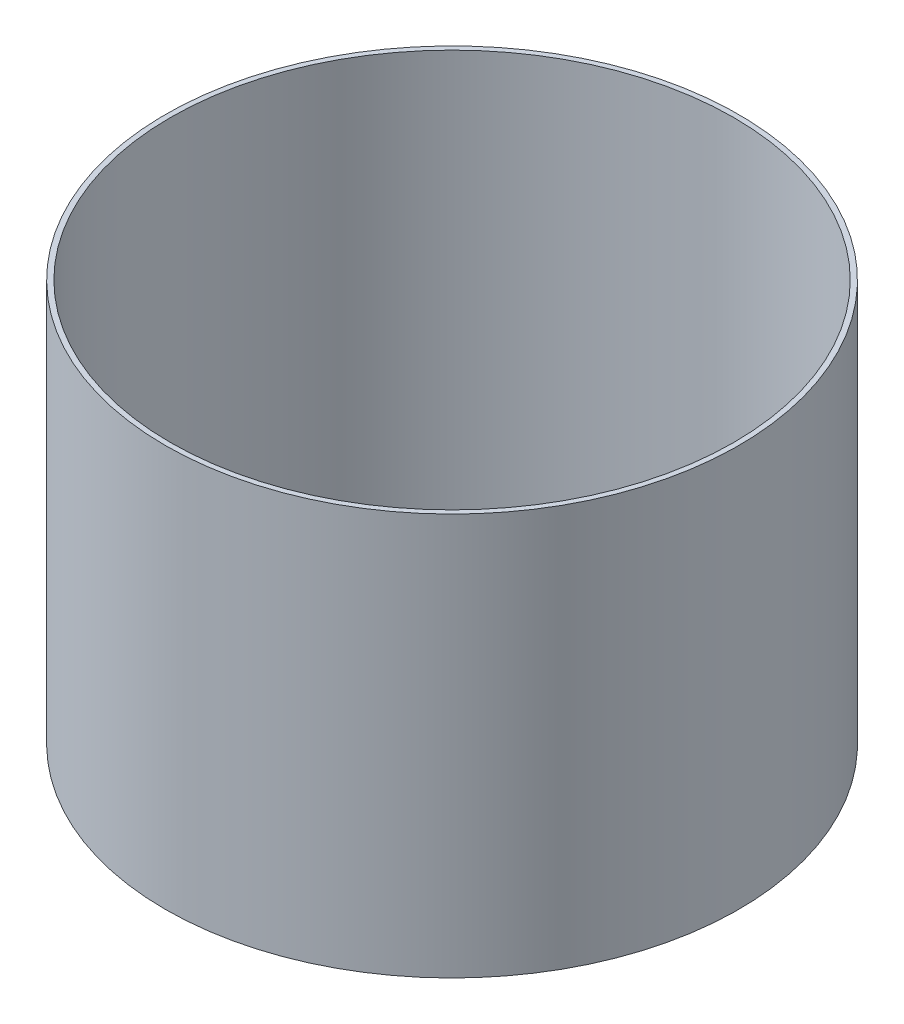
SolidWorks part; units mm, degrees
ref_plane "Front Plane" through (0, 0, 0) normal (0, 0, 1) x (1, 0, 0)
ref_plane "Top Plane" through (0, 0, 0) normal (0, 1, 0) x (1, 0, 0)
ref_plane "Right Plane" through (0, 0, 0) normal (1, 0, 0) x (0, 0, -1)
sketch "Sketch2" plane through (0, 0, 0) normal (0, 1, 0) x (1, 0, 0)
  circle A0 centre (0, 0) radius 71.12
  circle A1 centre (0, 0) radius 69.85
  dimension "D1" = 142.24
  dimension "D2" = 139.7
extrude "Extrude1" add sketch "Sketch2" against normal blind 99.6696
sketch "Sketch1" plane through (0, 0, 0) normal (0, 0, 1) x (1, 0, 0)
  line L1 (-228.6, 0) -> (228.6, 0)
  line L2 (-228.6, 0) -> (-228.6, -99.6718)
  line L3 (-228.6, -99.6718) -> (228.6, -99.6718)
  line L4 (228.6, 0) -> (228.6, -99.6718)
  line L416 (-215.864, -82.9078) -> (215.864, -82.9078) construction
  line L417 (215.864, -82.9078) -> (215.864, -66.7382) construction
  line L418 (215.864, -66.7382) -> (-215.864, -66.7382) construction
  line L419 (-215.864, -66.7382) -> (-215.864, -82.9078) construction
  line L420 (-202.6925, -66.7382) -> (-201.5763, -66.7382) construction
  line L421 (-201.5763, -66.7382) -> (-201.5763, -57.5942) construction
  line L422 (-201.5763, -57.5942) -> (-202.6925, -57.5942) construction
  line L423 (-202.6925, -57.5942) -> (-202.6925, -66.7382) construction
  line L424 (-175.7412, -66.7382) -> (-174.6251, -66.7382) construction
  line L425 (-174.6251, -66.7382) -> (-174.6251, -57.5942) construction
  line L426 (-174.6251, -57.5942) -> (-175.7412, -57.5942) construction
  line L427 (-175.7412, -57.5942) -> (-175.7412, -66.7382) construction
  line L428 (-148.79, -66.7382) -> (-147.6738, -66.7382) construction
  line L429 (-147.6738, -66.7382) -> (-147.6738, -57.5942) construction
  line L430 (-147.6738, -57.5942) -> (-148.79, -57.5942) construction
  line L431 (-148.79, -57.5942) -> (-148.79, -66.7382) construction
  line L432 (-121.8387, -66.7382) -> (-120.7225, -66.7382) construction
  line L433 (-120.7225, -66.7382) -> (-120.7225, -57.5942) construction
  line L434 (-120.7225, -57.5942) -> (-121.8387, -57.5942) construction
  line L435 (-121.8387, -57.5942) -> (-121.8387, -66.7382) construction
  line L436 (-94.8875, -66.7382) -> (-93.7713, -66.7382) construction
  line L437 (-93.7713, -66.7382) -> (-93.7713, -57.5942) construction
  line L438 (-93.7713, -57.5942) -> (-94.8875, -57.5942) construction
  line L439 (-94.8875, -57.5942) -> (-94.8875, -66.7382) construction
  line L440 (-67.9362, -66.7382) -> (-66.82, -66.7382) construction
  line L441 (-66.82, -66.7382) -> (-66.82, -57.5942) construction
  line L442 (-66.82, -57.5942) -> (-67.9362, -57.5942) construction
  line L443 (-67.9362, -57.5942) -> (-67.9362, -66.7382) construction
  line L444 (-40.985, -66.7382) -> (-39.8688, -66.7382) construction
  line L445 (-39.8688, -66.7382) -> (-39.8688, -57.5942) construction
  line L446 (-39.8688, -57.5942) -> (-40.985, -57.5942) construction
  line L447 (-40.985, -57.5942) -> (-40.985, -66.7382) construction
  line L448 (-14.0337, -66.7382) -> (-12.9175, -66.7382) construction
  line L449 (-12.9175, -66.7382) -> (-12.9175, -57.5942) construction
  line L450 (-12.9175, -57.5942) -> (-14.0337, -57.5942) construction
  line L451 (-14.0337, -57.5942) -> (-14.0337, -66.7382) construction
  line L452 (12.9175, -66.7382) -> (14.0337, -66.7382) construction
  line L453 (14.0337, -66.7382) -> (14.0337, -57.5942) construction
  line L454 (14.0337, -57.5942) -> (12.9175, -57.5942) construction
  line L455 (12.9175, -57.5942) -> (12.9175, -66.7382) construction
  line L456 (39.8688, -66.7382) -> (40.985, -66.7382) construction
  line L457 (40.985, -66.7382) -> (40.985, -57.5942) construction
  line L458 (40.985, -57.5942) -> (39.8688, -57.5942) construction
  line L459 (39.8688, -57.5942) -> (39.8688, -66.7382) construction
  line L460 (66.82, -66.7382) -> (67.9362, -66.7382) construction
  line L461 (67.9362, -66.7382) -> (67.9362, -57.5942) construction
  line L462 (67.9362, -57.5942) -> (66.82, -57.5942) construction
  line L463 (66.82, -57.5942) -> (66.82, -66.7382) construction
  line L464 (93.7713, -66.7382) -> (94.8875, -66.7382) construction
  line L465 (94.8875, -66.7382) -> (94.8875, -57.5942) construction
  line L466 (94.8875, -57.5942) -> (93.7713, -57.5942) construction
  line L467 (93.7713, -57.5942) -> (93.7713, -66.7382) construction
  line L468 (120.7225, -66.7382) -> (121.8387, -66.7382) construction
  line L469 (121.8387, -66.7382) -> (121.8387, -57.5942) construction
  line L470 (121.8387, -57.5942) -> (120.7225, -57.5942) construction
  line L471 (120.7225, -57.5942) -> (120.7225, -66.7382) construction
  line L472 (147.6738, -66.7382) -> (148.79, -66.7382) construction
  line L473 (148.79, -66.7382) -> (148.79, -57.5942) construction
  line L474 (148.79, -57.5942) -> (147.6738, -57.5942) construction
  line L475 (147.6738, -57.5942) -> (147.6738, -66.7382) construction
  line L476 (174.6251, -66.7382) -> (175.7412, -66.7382) construction
  line L477 (175.7412, -66.7382) -> (175.7412, -57.5942) construction
  line L478 (175.7412, -57.5942) -> (174.6251, -57.5942) construction
  line L479 (174.6251, -57.5942) -> (174.6251, -66.7382) construction
  line L480 (201.5763, -66.7382) -> (202.6925, -66.7382) construction
  line L481 (202.6925, -66.7382) -> (202.6925, -57.5942) construction
  line L482 (202.6925, -57.5942) -> (201.5763, -57.5942) construction
  line L483 (201.5763, -57.5942) -> (201.5763, -66.7382) construction
  line L484 (-201.5763, -57.5942) -> (-175.7412, -57.5942) construction
  line L485 (-175.7412, -57.5942) -> (-175.7412, -56.478) construction
  line L486 (-175.7412, -56.478) -> (-201.5763, -56.478) construction
  line L487 (-201.5763, -56.478) -> (-201.5763, -57.5942) construction
  line L488 (-147.6738, -57.5942) -> (-121.8387, -57.5942) construction
  line L489 (-121.8387, -57.5942) -> (-121.8387, -56.478) construction
  line L490 (-121.8387, -56.478) -> (-147.6738, -56.478) construction
  line L491 (-147.6738, -56.478) -> (-147.6738, -57.5942) construction
  line L492 (-93.7713, -57.5942) -> (-67.9361, -57.5942) construction
  line L493 (-67.9361, -57.5942) -> (-67.9361, -56.478) construction
  line L494 (-67.9361, -56.478) -> (-93.7713, -56.478) construction
  line L495 (-93.7713, -56.478) -> (-93.7713, -57.5942) construction
  line L496 (-39.8687, -57.5942) -> (-14.0336, -57.5942) construction
  line L497 (-14.0336, -57.5942) -> (-14.0336, -56.478) construction
  line L498 (-14.0336, -56.478) -> (-39.8687, -56.478) construction
  line L499 (-39.8687, -56.478) -> (-39.8687, -57.5942) construction
  line L500 (14.0336, -57.5942) -> (39.8687, -57.5942) construction
  line L501 (39.8687, -57.5942) -> (39.8687, -56.478) construction
  line L502 (39.8687, -56.478) -> (14.0336, -56.478) construction
  line L503 (14.0336, -56.478) -> (14.0336, -57.5942) construction
  line L504 (67.9361, -57.5942) -> (93.7713, -57.5942) construction
  line L505 (93.7713, -57.5942) -> (93.7713, -56.478) construction
  line L506 (93.7713, -56.478) -> (67.9361, -56.478) construction
  line L507 (67.9361, -56.478) -> (67.9361, -57.5942) construction
  line L508 (121.8387, -57.5942) -> (147.6738, -57.5942) construction
  line L509 (147.6738, -57.5942) -> (147.6738, -56.478) construction
  line L510 (147.6738, -56.478) -> (121.8387, -56.478) construction
  line L511 (121.8387, -56.478) -> (121.8387, -57.5942) construction
  line L512 (175.7412, -57.5942) -> (201.5763, -57.5942) construction
  line L513 (201.5763, -57.5942) -> (201.5763, -56.478) construction
  line L514 (201.5763, -56.478) -> (175.7412, -56.478) construction
  line L515 (175.7412, -56.478) -> (175.7412, -57.5942) construction
  line L516 (-190.8513, -57.5942) -> (-186.4661, -57.5942) construction
  line L517 (-186.4661, -57.5942) -> (-186.4661, -47.334) construction
  line L518 (-186.4661, -47.334) -> (-190.8513, -47.334) construction
  line L519 (-190.8513, -47.334) -> (-190.8513, -57.5942) construction
  line L520 (-136.9488, -57.5942) -> (-132.5636, -57.5942) construction
  line L521 (-132.5636, -57.5942) -> (-132.5636, -47.334) construction
  line L522 (-132.5636, -47.334) -> (-136.9488, -47.334) construction
  line L523 (-136.9488, -47.334) -> (-136.9488, -57.5942) construction
  line L524 (-83.0464, -57.5942) -> (-78.6611, -57.5942) construction
  line L525 (-78.6611, -57.5942) -> (-78.6611, -47.334) construction
  line L526 (-78.6611, -47.334) -> (-83.0464, -47.334) construction
  line L527 (-83.0464, -47.334) -> (-83.0464, -57.5942) construction
  line L528 (-29.1439, -57.5942) -> (-24.7585, -57.5942) construction
  line L529 (-24.7585, -57.5942) -> (-24.7585, -47.334) construction
  line L530 (-24.7585, -47.334) -> (-29.1439, -47.334) construction
  line L531 (-29.1439, -47.334) -> (-29.1439, -57.5942) construction
  line L532 (24.7585, -57.5942) -> (29.1439, -57.5942) construction
  line L533 (29.1439, -57.5942) -> (29.1439, -47.334) construction
  line L534 (29.1439, -47.334) -> (24.7585, -47.334) construction
  line L535 (24.7585, -47.334) -> (24.7585, -57.5942) construction
  line L536 (78.6611, -57.5942) -> (83.0464, -57.5942) construction
  line L537 (83.0464, -57.5942) -> (83.0464, -47.334) construction
  line L538 (83.0464, -47.334) -> (78.6611, -47.334) construction
  line L539 (78.6611, -47.334) -> (78.6611, -57.5942) construction
  line L540 (132.5636, -57.5942) -> (136.9488, -57.5942) construction
  line L541 (136.9488, -57.5942) -> (136.9488, -47.334) construction
  line L542 (136.9488, -47.334) -> (132.5636, -47.334) construction
  line L543 (132.5636, -47.334) -> (132.5636, -57.5942) construction
  line L544 (186.4661, -57.5942) -> (190.8513, -57.5942) construction
  line L545 (190.8513, -57.5942) -> (190.8513, -47.334) construction
  line L546 (190.8513, -47.334) -> (186.4661, -47.334) construction
  line L547 (186.4661, -47.334) -> (186.4661, -57.5942) construction
  line L548 (-186.466, -47.334) -> (-177.9096, -47.334) construction
  line L549 (-177.9096, -47.334) -> (-177.9096, -42.9487) construction
  line L550 (-177.9096, -42.9487) -> (-186.466, -42.9487) construction
  line L551 (-186.466, -42.9487) -> (-186.466, -47.334) construction
  line L552 (-145.5055, -47.334) -> (-136.9489, -47.334) construction
  line L553 (-136.9489, -47.334) -> (-136.9489, -42.9487) construction
  line L554 (-136.9489, -42.9487) -> (-145.5055, -42.9487) construction
  line L555 (-145.5055, -42.9487) -> (-145.5055, -47.334) construction
  line L556 (-78.6611, -47.334) -> (-70.1045, -47.334) construction
  line L557 (-70.1045, -47.334) -> (-70.1045, -42.9487) construction
  line L558 (-70.1045, -42.9487) -> (-78.6611, -42.9487) construction
  line L559 (-78.6611, -42.9487) -> (-78.6611, -47.334) construction
  line L560 (-37.7005, -47.334) -> (-29.1439, -47.334) construction
  line L561 (-29.1439, -47.334) -> (-29.1439, -42.9487) construction
  line L562 (-29.1439, -42.9487) -> (-37.7005, -42.9487) construction
  line L563 (-37.7005, -42.9487) -> (-37.7005, -47.334) construction
  line L564 (29.1439, -47.334) -> (37.7005, -47.334) construction
  line L565 (37.7005, -47.334) -> (37.7005, -42.9487) construction
  line L566 (37.7005, -42.9487) -> (29.1439, -42.9487) construction
  line L567 (29.1439, -42.9487) -> (29.1439, -47.334) construction
  line L568 (70.1045, -47.334) -> (78.6611, -47.334) construction
  line L569 (78.6611, -47.334) -> (78.6611, -42.9487) construction
  line L570 (78.6611, -42.9487) -> (70.1045, -42.9487) construction
  line L571 (70.1045, -42.9487) -> (70.1045, -47.334) construction
  line L572 (136.9489, -47.334) -> (145.5055, -47.334) construction
  line L573 (145.5055, -47.334) -> (145.5055, -42.9487) construction
  line L574 (145.5055, -42.9487) -> (136.9489, -42.9487) construction
  line L575 (136.9489, -42.9487) -> (136.9489, -47.334) construction
  line L576 (177.9096, -47.334) -> (186.466, -47.334) construction
  line L577 (186.466, -47.334) -> (186.466, -42.9487) construction
  line L578 (186.466, -42.9487) -> (177.9096, -42.9487) construction
  line L579 (177.9096, -42.9487) -> (177.9096, -47.334) construction
  line L580 (-177.9095, -46.538) -> (-168.0714, -46.538) construction
  line L581 (-168.0714, -46.538) -> (-168.0714, -43.7446) construction
  line L582 (-168.0714, -43.7446) -> (-177.9095, -43.7446) construction
  line L583 (-177.9095, -43.7446) -> (-177.9095, -46.538) construction
  line L584 (-155.3435, -46.538) -> (-145.5054, -46.538) construction
  line L585 (-145.5054, -46.538) -> (-145.5054, -43.7446) construction
  line L586 (-145.5054, -43.7446) -> (-155.3435, -43.7446) construction
  line L587 (-155.3435, -43.7446) -> (-155.3435, -46.538) construction
  line L588 (-70.1045, -46.538) -> (-60.2665, -46.538) construction
  line L589 (-60.2665, -46.538) -> (-60.2665, -43.7446) construction
  line L590 (-60.2665, -43.7446) -> (-70.1045, -43.7446) construction
  line L591 (-70.1045, -43.7446) -> (-70.1045, -46.538) construction
  line L592 (-47.5385, -46.538) -> (-37.7005, -46.538) construction
  line L593 (-37.7005, -46.538) -> (-37.7005, -43.7446) construction
  line L594 (-37.7005, -43.7446) -> (-47.5385, -43.7446) construction
  line L595 (-47.5385, -43.7446) -> (-47.5385, -46.538) construction
  line L596 (37.7005, -46.538) -> (47.5385, -46.538) construction
  line L597 (47.5385, -46.538) -> (47.5385, -43.7446) construction
  line L598 (47.5385, -43.7446) -> (37.7005, -43.7446) construction
  line L599 (37.7005, -43.7446) -> (37.7005, -46.538) construction
  line L600 (60.2665, -46.538) -> (70.1045, -46.538) construction
  line L601 (70.1045, -46.538) -> (70.1045, -43.7446) construction
  line L602 (70.1045, -43.7446) -> (60.2665, -43.7446) construction
  line L603 (60.2665, -43.7446) -> (60.2665, -46.538) construction
  line L604 (145.5054, -46.538) -> (155.3435, -46.538) construction
  line L605 (155.3435, -46.538) -> (155.3435, -43.7446) construction
  line L606 (155.3435, -43.7446) -> (145.5054, -43.7446) construction
  line L607 (145.5054, -43.7446) -> (145.5054, -46.538) construction
  line L608 (168.0714, -46.538) -> (177.9095, -46.538) construction
  line L609 (177.9095, -46.538) -> (177.9095, -43.7446) construction
  line L610 (177.9095, -43.7446) -> (168.0714, -43.7446) construction
  line L611 (168.0714, -43.7446) -> (168.0714, -46.538) construction
  line L612 (-168.0714, -45.9607) -> (-155.3436, -45.9607) construction
  line L613 (-155.3436, -45.9607) -> (-155.3436, -44.322) construction
  line L614 (-155.3436, -44.322) -> (-168.0714, -44.322) construction
  line L615 (-168.0714, -44.322) -> (-168.0714, -45.9607) construction
  line L616 (-60.2665, -45.9607) -> (-47.5385, -45.9607) construction
  line L617 (-47.5385, -45.9607) -> (-47.5385, -44.322) construction
  line L618 (-47.5385, -44.322) -> (-60.2665, -44.322) construction
  line L619 (-60.2665, -44.322) -> (-60.2665, -45.9607) construction
  line L620 (47.5385, -45.9607) -> (60.2665, -45.9607) construction
  line L621 (60.2665, -45.9607) -> (60.2665, -44.322) construction
  line L622 (60.2665, -44.322) -> (47.5385, -44.322) construction
  line L623 (47.5385, -44.322) -> (47.5385, -45.9607) construction
  line L624 (155.3436, -45.9607) -> (168.0714, -45.9607) construction
  line L625 (168.0714, -45.9607) -> (168.0714, -44.322) construction
  line L626 (168.0714, -44.322) -> (155.3436, -44.322) construction
  line L627 (155.3436, -44.322) -> (155.3436, -45.9607) construction
  line L628 (-164.5244, -44.322) -> (-158.8906, -44.322) construction
  line L629 (-158.8906, -44.322) -> (-158.8906, -35.178) construction
  line L630 (-158.8906, -35.178) -> (-164.5244, -35.178) construction
  line L631 (-164.5244, -35.178) -> (-164.5244, -44.322) construction
  line L632 (-56.7194, -44.322) -> (-51.0856, -44.322) construction
  line L633 (-51.0856, -44.322) -> (-51.0856, -35.178) construction
  line L634 (-51.0856, -35.178) -> (-56.7194, -35.178) construction
  line L635 (-56.7194, -35.178) -> (-56.7194, -44.322) construction
  line L636 (51.0856, -44.322) -> (56.7194, -44.322) construction
  line L637 (56.7194, -44.322) -> (56.7194, -35.178) construction
  line L638 (56.7194, -35.178) -> (51.0856, -35.178) construction
  line L639 (51.0856, -35.178) -> (51.0856, -44.322) construction
  line L640 (158.8906, -44.322) -> (164.5244, -44.322) construction
  line L641 (164.5244, -44.322) -> (164.5244, -35.178) construction
  line L642 (164.5244, -35.178) -> (158.8906, -35.178) construction
  line L643 (158.8906, -35.178) -> (158.8906, -44.322) construction
  line L644 (-158.8906, -35.178) -> (-131.3922, -35.178) construction
  line L645 (-131.3922, -35.178) -> (-131.3922, -29.5443) construction
  line L646 (-131.3922, -29.5443) -> (-158.8906, -29.5443) construction
  line L647 (-158.8906, -29.5443) -> (-158.8906, -35.178) construction
  line L648 (-84.2178, -35.178) -> (-56.7194, -35.178) construction
  line L649 (-56.7194, -35.178) -> (-56.7194, -29.5443) construction
  line L650 (-56.7194, -29.5443) -> (-84.2178, -29.5443) construction
  line L651 (-84.2178, -29.5443) -> (-84.2178, -35.178) construction
  line L652 (56.7194, -35.178) -> (84.2178, -35.178) construction
  line L653 (84.2178, -35.178) -> (84.2178, -29.5443) construction
  line L654 (84.2178, -29.5443) -> (56.7194, -29.5443) construction
  line L655 (56.7194, -29.5443) -> (56.7194, -35.178) construction
  line L656 (131.3922, -35.178) -> (158.8906, -35.178) construction
  line L657 (158.8906, -35.178) -> (158.8906, -29.5443) construction
  line L658 (158.8906, -29.5443) -> (131.3922, -29.5443) construction
  line L659 (131.3922, -29.5443) -> (131.3922, -35.178) construction
  line L660 (-131.3922, -33.9769) -> (-121.3448, -33.9769) construction
  line L661 (-121.3448, -33.9769) -> (-121.3448, -30.7453) construction
  line L662 (-121.3448, -30.7453) -> (-131.3922, -30.7453) construction
  line L663 (-131.3922, -30.7453) -> (-131.3922, -33.9769) construction
  line L664 (-94.2652, -33.9769) -> (-84.2178, -33.9769) construction
  line L665 (-84.2178, -33.9769) -> (-84.2178, -30.7453) construction
  line L666 (-84.2178, -30.7453) -> (-94.2652, -30.7453) construction
  line L667 (-94.2652, -30.7453) -> (-94.2652, -33.9769) construction
  line L668 (84.2178, -33.9769) -> (94.2652, -33.9769) construction
  line L669 (94.2652, -33.9769) -> (94.2652, -30.7453) construction
  line L670 (94.2652, -30.7453) -> (84.2178, -30.7453) construction
  line L671 (84.2178, -30.7453) -> (84.2178, -33.9769) construction
  line L672 (121.3448, -33.9769) -> (131.3922, -33.9769) construction
  line L673 (131.3922, -33.9769) -> (131.3922, -30.7453) construction
  line L674 (131.3922, -30.7453) -> (121.3448, -30.7453) construction
  line L675 (121.3448, -30.7453) -> (121.3448, -33.9769) construction
  line L676 (-121.3448, -33.1804) -> (-94.2652, -33.1804) construction
  line L677 (-94.2652, -33.1804) -> (-94.2652, -31.5418) construction
  line L678 (-94.2652, -31.5418) -> (-121.3448, -31.5418) construction
  line L679 (-121.3448, -31.5418) -> (-121.3448, -33.1804) construction
  line L680 (94.2652, -33.1804) -> (121.3448, -33.1804) construction
  line L681 (121.3448, -33.1804) -> (121.3448, -31.5418) construction
  line L682 (121.3448, -31.5418) -> (94.2652, -31.5418) construction
  line L683 (94.2652, -31.5418) -> (94.2652, -33.1804) construction
  line L684 (-110.6219, -31.5418) -> (-104.9881, -31.5418) construction
  line L685 (-104.9881, -31.5418) -> (-104.9881, -22.3978) construction
  line L686 (-104.9881, -22.3978) -> (-110.6219, -22.3978) construction
  line L687 (-110.6219, -22.3978) -> (-110.6219, -31.5418) construction
  line L688 (104.9881, -31.5418) -> (110.6219, -31.5418) construction
  line L689 (110.6219, -31.5418) -> (110.6219, -22.3978) construction
  line L690 (110.6219, -22.3978) -> (104.9881, -22.3978) construction
  line L691 (104.9881, -22.3978) -> (104.9881, -31.5418) construction
  line L692 (-104.9881, -22.3978) -> (-41.5547, -22.3978) construction
  line L693 (-41.5547, -22.3978) -> (-41.5547, -16.764) construction
  line L694 (-41.5547, -16.764) -> (-104.9881, -16.764) construction
  line L695 (-104.9881, -16.764) -> (-104.9881, -22.3978) construction
  line L696 (41.5547, -22.3978) -> (104.9881, -22.3978) construction
  line L697 (104.9881, -22.3978) -> (104.9881, -16.764) construction
  line L698 (104.9881, -16.764) -> (41.5547, -16.764) construction
  line L699 (41.5547, -16.764) -> (41.5547, -22.3978) construction
  line L700 (-41.5547, -21.1967) -> (-31.5072, -21.1967) construction
  line L701 (-31.5072, -21.1967) -> (-31.5072, -17.9651) construction
  line L702 (-31.5072, -17.9651) -> (-41.5547, -17.9651) construction
  line L703 (-41.5547, -17.9651) -> (-41.5547, -21.1967) construction
  line L704 (31.5072, -21.1967) -> (41.5547, -21.1967) construction
  line L705 (41.5547, -21.1967) -> (41.5547, -17.9651) construction
  line L706 (41.5547, -17.9651) -> (31.5072, -17.9651) construction
  line L707 (31.5072, -17.9651) -> (31.5072, -21.1967) construction
  line L708 (-31.5073, -20.4003) -> (31.5073, -20.4003) construction
  line L709 (31.5073, -20.4003) -> (31.5073, -18.7616) construction
  line L710 (31.5073, -18.7616) -> (-31.5073, -18.7616) construction
  line L711 (-31.5073, -18.7616) -> (-31.5073, -20.4003) construction
  line L712 (-202.1344, -57.5942) -> (-201.5762, -57.5942) construction
  line L713 (-201.5762, -57.5942) -> (-201.5762, -57.0361) construction
  line L714 (-201.5762, -57.0361) -> (-202.1344, -57.0361) construction
  line L715 (-202.1344, -57.0361) -> (-202.1344, -57.5942) construction
  line L716 (-175.7412, -57.5942) -> (-175.183, -57.5942) construction
  line L717 (-175.183, -57.5942) -> (-175.183, -57.0361) construction
  line L718 (-175.183, -57.0361) -> (-175.7412, -57.0361) construction
  line L719 (-175.7412, -57.0361) -> (-175.7412, -57.5942) construction
  line L720 (-148.2319, -57.5942) -> (-147.6737, -57.5942) construction
  line L721 (-147.6737, -57.5942) -> (-147.6737, -57.0361) construction
  line L722 (-147.6737, -57.0361) -> (-148.2319, -57.0361) construction
  line L723 (-148.2319, -57.0361) -> (-148.2319, -57.5942) construction
  line L724 (-121.8387, -57.5942) -> (-121.2806, -57.5942) construction
  line L725 (-121.2806, -57.5942) -> (-121.2806, -57.0361) construction
  line L726 (-121.2806, -57.0361) -> (-121.8387, -57.0361) construction
  line L727 (-121.8387, -57.0361) -> (-121.8387, -57.5942) construction
  line L728 (-94.3293, -57.5942) -> (-93.7712, -57.5942) construction
  line L729 (-93.7712, -57.5942) -> (-93.7712, -57.0361) construction
  line L730 (-93.7712, -57.0361) -> (-94.3293, -57.0361) construction
  line L731 (-94.3293, -57.0361) -> (-94.3293, -57.5942) construction
  line L732 (-67.9361, -57.5942) -> (-67.3781, -57.5942) construction
  line L733 (-67.3781, -57.5942) -> (-67.3781, -57.0361) construction
  line L734 (-67.3781, -57.0361) -> (-67.9361, -57.0361) construction
  line L735 (-67.9361, -57.0361) -> (-67.9361, -57.5942) construction
  line L736 (-40.4268, -57.5942) -> (-39.8687, -57.5942) construction
  line L737 (-39.8687, -57.5942) -> (-39.8687, -57.0361) construction
  line L738 (-39.8687, -57.0361) -> (-40.4268, -57.0361) construction
  line L739 (-40.4268, -57.0361) -> (-40.4268, -57.5942) construction
  line L740 (-14.0336, -57.5942) -> (-13.4756, -57.5942) construction
  line L741 (-13.4756, -57.5942) -> (-13.4756, -57.0361) construction
  line L742 (-13.4756, -57.0361) -> (-14.0336, -57.0361) construction
  line L743 (-14.0336, -57.0361) -> (-14.0336, -57.5942) construction
  line L744 (13.4756, -57.5942) -> (14.0336, -57.5942) construction
  line L745 (14.0336, -57.5942) -> (14.0336, -57.0361) construction
  line L746 (14.0336, -57.0361) -> (13.4756, -57.0361) construction
  line L747 (13.4756, -57.0361) -> (13.4756, -57.5942) construction
  line L748 (39.8687, -57.5942) -> (40.4268, -57.5942) construction
  line L749 (40.4268, -57.5942) -> (40.4268, -57.0361) construction
  line L750 (40.4268, -57.0361) -> (39.8687, -57.0361) construction
  line L751 (39.8687, -57.0361) -> (39.8687, -57.5942) construction
  line L752 (67.3781, -57.5942) -> (67.9361, -57.5942) construction
  line L753 (67.9361, -57.5942) -> (67.9361, -57.0361) construction
  line L754 (67.9361, -57.0361) -> (67.3781, -57.0361) construction
  line L755 (67.3781, -57.0361) -> (67.3781, -57.5942) construction
  line L756 (93.7712, -57.5942) -> (94.3293, -57.5942) construction
  line L757 (94.3293, -57.5942) -> (94.3293, -57.0361) construction
  line L758 (94.3293, -57.0361) -> (93.7712, -57.0361) construction
  line L759 (93.7712, -57.0361) -> (93.7712, -57.5942) construction
  line L760 (121.2806, -57.5942) -> (121.8387, -57.5942) construction
  line L761 (121.8387, -57.5942) -> (121.8387, -57.0361) construction
  line L762 (121.8387, -57.0361) -> (121.2806, -57.0361) construction
  line L763 (121.2806, -57.0361) -> (121.2806, -57.5942) construction
  line L764 (147.6737, -57.5942) -> (148.2319, -57.5942) construction
  line L765 (148.2319, -57.5942) -> (148.2319, -57.0361) construction
  line L766 (148.2319, -57.0361) -> (147.6737, -57.0361) construction
  line L767 (147.6737, -57.0361) -> (147.6737, -57.5942) construction
  line L768 (175.183, -57.5942) -> (175.7412, -57.5942) construction
  line L769 (175.7412, -57.5942) -> (175.7412, -57.0361) construction
  line L770 (175.7412, -57.0361) -> (175.183, -57.0361) construction
  line L771 (175.183, -57.0361) -> (175.183, -57.5942) construction
  line L772 (201.5762, -57.5942) -> (202.1344, -57.5942) construction
  line L773 (202.1344, -57.5942) -> (202.1344, -57.0361) construction
  line L774 (202.1344, -57.0361) -> (201.5762, -57.0361) construction
  line L775 (201.5762, -57.0361) -> (201.5762, -57.5942) construction
  line L776 (-188.6588, -47.334) -> (-186.466, -47.334) construction
  line L777 (-186.466, -47.334) -> (-186.466, -45.1412) construction
  line L778 (-186.466, -45.1412) -> (-188.6588, -45.1412) construction
  line L779 (-188.6588, -45.1412) -> (-188.6588, -47.334) construction
  line L780 (-136.9489, -47.334) -> (-134.7563, -47.334) construction
  line L781 (-134.7563, -47.334) -> (-134.7563, -45.1412) construction
  line L782 (-134.7563, -45.1412) -> (-136.9489, -45.1412) construction
  line L783 (-136.9489, -45.1412) -> (-136.9489, -47.334) construction
  line L784 (-80.8538, -47.334) -> (-78.6611, -47.334) construction
  line L785 (-78.6611, -47.334) -> (-78.6611, -45.1412) construction
  line L786 (-78.6611, -45.1412) -> (-80.8538, -45.1412) construction
  line L787 (-80.8538, -45.1412) -> (-80.8538, -47.334) construction
  line L788 (-29.1439, -47.334) -> (-26.9513, -47.334) construction
  line L789 (-26.9513, -47.334) -> (-26.9513, -45.1412) construction
  line L790 (-26.9513, -45.1412) -> (-29.1439, -45.1412) construction
  line L791 (-29.1439, -45.1412) -> (-29.1439, -47.334) construction
  line L792 (26.9513, -47.334) -> (29.1439, -47.334) construction
  line L793 (29.1439, -47.334) -> (29.1439, -45.1412) construction
  line L794 (29.1439, -45.1412) -> (26.9513, -45.1412) construction
  line L795 (26.9513, -45.1412) -> (26.9513, -47.334) construction
  line L796 (78.6611, -47.334) -> (80.8538, -47.334) construction
  line L797 (80.8538, -47.334) -> (80.8538, -45.1412) construction
  line L798 (80.8538, -45.1412) -> (78.6611, -45.1412) construction
  line L799 (78.6611, -45.1412) -> (78.6611, -47.334) construction
  line L800 (134.7563, -47.334) -> (136.9489, -47.334) construction
  line L801 (136.9489, -47.334) -> (136.9489, -45.1412) construction
  line L802 (136.9489, -45.1412) -> (134.7563, -45.1412) construction
  line L803 (134.7563, -45.1412) -> (134.7563, -47.334) construction
  line L804 (186.466, -47.334) -> (188.6588, -47.334) construction
  line L805 (188.6588, -47.334) -> (188.6588, -45.1412) construction
  line L806 (188.6588, -45.1412) -> (186.466, -45.1412) construction
  line L807 (186.466, -45.1412) -> (186.466, -47.334) construction
  line L808 (-161.7074, -35.178) -> (-158.8906, -35.178) construction
  line L809 (-158.8906, -35.178) -> (-158.8906, -32.3611) construction
  line L810 (-158.8906, -32.3611) -> (-161.7074, -32.3611) construction
  line L811 (-161.7074, -32.3611) -> (-161.7074, -35.178) construction
  line L812 (-56.7193, -35.178) -> (-53.9024, -35.178) construction
  line L813 (-53.9024, -35.178) -> (-53.9024, -32.3611) construction
  line L814 (-53.9024, -32.3611) -> (-56.7193, -32.3611) construction
  line L815 (-56.7193, -32.3611) -> (-56.7193, -35.178) construction
  line L816 (53.9024, -35.178) -> (56.7193, -35.178) construction
  line L817 (56.7193, -35.178) -> (56.7193, -32.3611) construction
  line L818 (56.7193, -32.3611) -> (53.9024, -32.3611) construction
  line L819 (53.9024, -32.3611) -> (53.9024, -35.178) construction
  line L820 (158.8906, -35.178) -> (161.7074, -35.178) construction
  line L821 (161.7074, -35.178) -> (161.7074, -32.3611) construction
  line L822 (161.7074, -32.3611) -> (158.8906, -32.3611) construction
  line L823 (158.8906, -32.3611) -> (158.8906, -35.178) construction
  line L824 (-107.805, -22.3977) -> (-104.9881, -22.3977) construction
  line L825 (-104.9881, -22.3977) -> (-104.9881, -19.5809) construction
  line L826 (-104.9881, -19.5809) -> (-107.805, -19.5809) construction
  line L827 (-107.805, -19.5809) -> (-107.805, -22.3977) construction
  line L828 (104.9881, -22.3977) -> (107.805, -22.3977) construction
  line L829 (107.805, -22.3977) -> (107.805, -19.5809) construction
  line L830 (107.805, -19.5809) -> (104.9881, -19.5809) construction
  line L831 (104.9881, -19.5809) -> (104.9881, -22.3977) construction
  line L832 (-228.6, 0) -> (228.6, 0) construction
  line L866 (-228.6, -99.6718) -> (228.6, -99.6718) construction
  line L867 (-228.6, 0) -> (228.6, 0) construction
  line L868 (218.15, -9.144) -> (218.15, -57.5942) construction
  line L869 (-218.15, -9.144) -> (-218.15, -57.5942) construction
  line L870 (-202.4134, -57.5942) -> (-201.5763, -56.757) construction
  line L871 (-175.7412, -56.757) -> (-174.9041, -57.5942) construction
  line L872 (-148.5109, -57.5942) -> (-147.6738, -56.757) construction
  line L873 (-121.8387, -56.757) -> (-121.0016, -57.5942) construction
  line L874 (-94.6084, -57.5942) -> (-93.7713, -56.757) construction
  line L875 (-67.9362, -56.757) -> (-67.0991, -57.5942) construction
  line L876 (-40.7059, -57.5942) -> (-39.8688, -56.757) construction
  line L877 (-14.0337, -56.757) -> (-13.1966, -57.5942) construction
  line L878 (13.1966, -57.5942) -> (14.0337, -56.757) construction
  line L879 (39.8688, -56.757) -> (40.7059, -57.5942) construction
  line L880 (67.0991, -57.5942) -> (67.9362, -56.757) construction
  line L881 (93.7713, -56.757) -> (94.6084, -57.5942) construction
  line L882 (121.0016, -57.5942) -> (121.8387, -56.757) construction
  line L883 (147.6738, -56.757) -> (148.5109, -57.5942) construction
  line L884 (174.9041, -57.5942) -> (175.7412, -56.757) construction
  line L885 (201.5763, -56.757) -> (202.4134, -57.5942) construction
  line L886 (-189.7551, -47.334) -> (-186.4661, -44.045) construction
  line L887 (-136.9489, -44.045) -> (-133.66, -47.334) construction
  line L888 (-81.9501, -47.334) -> (-78.6611, -44.045) construction
  line L889 (-29.1439, -44.045) -> (-25.8549, -47.334) construction
  line L890 (25.8549, -47.334) -> (29.1439, -44.045) construction
  line L891 (78.6611, -44.045) -> (81.9501, -47.334) construction
  line L892 (133.66, -47.334) -> (136.9489, -44.045) construction
  line L893 (186.4661, -44.045) -> (189.7551, -47.334) construction
  line L894 (-163.116, -35.178) -> (-158.8906, -30.9527) construction
  line L895 (-56.7194, -30.9527) -> (-52.4941, -35.178) construction
  line L896 (52.4941, -35.178) -> (56.7194, -30.9527) construction
  line L897 (158.8906, -30.9527) -> (163.116, -35.178) construction
  line L898 (-109.2134, -22.3978) -> (-104.9881, -18.1725) construction
  line L899 (104.9881, -18.1725) -> (109.2134, -22.3978) construction
  circle A25 centre (210.53, -94.5918) radius 2.54 construction
  circle A26 centre (107.805, -94.5918) radius 2.54 construction
  circle A27 centre (0, -94.5918) radius 2.54 construction
  circle A28 centre (-107.805, -94.5918) radius 2.54 construction
  circle A29 centre (-210.53, -94.5918) radius 2.54 construction
  circle A30 centre (210.53, -5.08) radius 2.54 construction
  circle A31 centre (107.805, -5.08) radius 2.54 construction
  circle A32 centre (0, -5.08) radius 2.54 construction
  circle A33 centre (-107.805, -5.08) radius 2.54 construction
  circle A34 centre (-210.53, -5.08) radius 2.54 construction
  circle A35 centre (210.53, -49.8359) radius 2.54 construction
  circle A36 centre (-210.53, -49.8359) radius 2.54 construction
  circle A37 centre (0, -19.5809) radius 6.35 construction
  circle A38 centre (210.53, -94.5918) radius 1.1303 construction
  circle A39 centre (107.805, -94.5918) radius 1.1303 construction
  circle A40 centre (0, -94.5918) radius 1.1303 construction
  circle A41 centre (-107.805, -94.5918) radius 1.1303 construction
  circle A42 centre (-210.53, -94.5918) radius 1.1303 construction
  circle A43 centre (210.53, -5.08) radius 1.1303 construction
  circle A44 centre (107.805, -5.08) radius 1.1303 construction
  circle A45 centre (0, -5.08) radius 1.1303 construction
  circle A46 centre (-107.805, -5.08) radius 1.1303 construction
  circle A47 centre (-210.53, -5.08) radius 1.1303 construction
  circle A48 centre (210.53, -49.8359) radius 1.1303 construction
  circle A49 centre (-210.53, -49.8359) radius 1.1303 construction
  circle A62 centre (210.53, -94.5918) radius 0.635 construction
  circle A63 centre (107.805, -94.5918) radius 0.635 construction
  circle A64 centre (0, -94.5918) radius 0.635 construction
  circle A65 centre (-107.805, -94.5918) radius 0.635 construction
  circle A66 centre (-210.53, -94.5918) radius 0.635 construction
  circle A67 centre (210.53, -5.08) radius 0.635 construction
  circle A68 centre (107.805, -5.08) radius 0.635 construction
  circle A69 centre (0, -5.08) radius 0.635 construction
  circle A70 centre (-107.805, -5.08) radius 0.635 construction
  circle A71 centre (-210.53, -5.08) radius 0.635 construction
  circle A72 centre (210.53, -49.8359) radius 0.635 construction
  circle A73 centre (-210.53, -49.8359) radius 0.635 construction
  circle A144 centre (0, -19.5809) radius 0.4762 construction
  circle A145 centre (0, -19.5809) radius 0.4762 construction
  arc A147 (-228.6, -99.6083) -> (-228.6, -99.7353) centre (-228.6, -99.6718) ccw construction
  arc A150 (217.515, -57.5942) -> (218.785, -57.5942) centre (218.15, -57.5942) ccw construction
  arc A151 (218.785, -9.144) -> (217.515, -9.144) centre (218.15, -9.144) ccw construction
  arc A152 (-218.785, -57.5942) -> (-217.515, -57.5942) centre (-218.15, -57.5942) ccw construction
  arc A153 (-217.515, -9.144) -> (-218.785, -9.144) centre (-218.15, -9.144) ccw construction
  arc A154 (-201.4777, -56.8556) -> (-201.6749, -56.6584) centre (-201.5763, -56.757) ccw construction
  arc A155 (-202.512, -57.4956) -> (-202.3148, -57.6928) centre (-202.4134, -57.5942) ccw construction
  arc A156 (-175.0027, -57.6928) -> (-174.8055, -57.4956) centre (-174.9041, -57.5942) ccw construction
  arc A157 (-175.6426, -56.6584) -> (-175.8398, -56.8556) centre (-175.7412, -56.757) ccw construction
  arc A158 (-147.5752, -56.8556) -> (-147.7724, -56.6584) centre (-147.6738, -56.757) ccw construction
  arc A159 (-148.6095, -57.4956) -> (-148.4123, -57.6928) centre (-148.5109, -57.5942) ccw construction
  arc A160 (-121.1002, -57.6928) -> (-120.903, -57.4956) centre (-121.0016, -57.5942) ccw construction
  arc A161 (-121.7401, -56.6584) -> (-121.9373, -56.8556) centre (-121.8387, -56.757) ccw construction
  arc A162 (-93.6727, -56.8556) -> (-93.8699, -56.6584) centre (-93.7713, -56.757) ccw construction
  arc A163 (-94.707, -57.4956) -> (-94.5098, -57.6928) centre (-94.6084, -57.5942) ccw construction
  arc A164 (-67.1977, -57.6928) -> (-67.0005, -57.4956) centre (-67.0991, -57.5942) ccw construction
  arc A165 (-67.8376, -56.6584) -> (-68.0348, -56.8556) centre (-67.9362, -56.757) ccw construction
  arc A166 (-39.7702, -56.8556) -> (-39.9674, -56.6584) centre (-39.8688, -56.757) ccw construction
  arc A167 (-40.8045, -57.4956) -> (-40.6073, -57.6928) centre (-40.7059, -57.5942) ccw construction
  arc A168 (-13.2952, -57.6928) -> (-13.098, -57.4956) centre (-13.1966, -57.5942) ccw construction
  arc A169 (-13.9351, -56.6584) -> (-14.1323, -56.8556) centre (-14.0337, -56.757) ccw construction
  arc A170 (14.1323, -56.8556) -> (13.9351, -56.6584) centre (14.0337, -56.757) ccw construction
  arc A171 (13.098, -57.4956) -> (13.2952, -57.6928) centre (13.1966, -57.5942) ccw construction
  arc A172 (40.6073, -57.6928) -> (40.8045, -57.4956) centre (40.7059, -57.5942) ccw construction
  arc A173 (39.9674, -56.6584) -> (39.7702, -56.8556) centre (39.8688, -56.757) ccw construction
  arc A174 (68.0348, -56.8556) -> (67.8376, -56.6584) centre (67.9362, -56.757) ccw construction
  arc A175 (67.0005, -57.4956) -> (67.1977, -57.6928) centre (67.0991, -57.5942) ccw construction
  arc A176 (94.5098, -57.6928) -> (94.707, -57.4956) centre (94.6084, -57.5942) ccw construction
  arc A177 (93.8699, -56.6584) -> (93.6727, -56.8556) centre (93.7713, -56.757) ccw construction
  arc A178 (121.9373, -56.8556) -> (121.7401, -56.6584) centre (121.8387, -56.757) ccw construction
  arc A179 (120.903, -57.4956) -> (121.1002, -57.6928) centre (121.0016, -57.5942) ccw construction
  arc A180 (148.4123, -57.6928) -> (148.6095, -57.4956) centre (148.5109, -57.5942) ccw construction
  arc A181 (147.7724, -56.6584) -> (147.5752, -56.8556) centre (147.6738, -56.757) ccw construction
  arc A182 (175.8398, -56.8556) -> (175.6426, -56.6584) centre (175.7412, -56.757) ccw construction
  arc A183 (174.8055, -57.4956) -> (175.0027, -57.6928) centre (174.9041, -57.5942) ccw construction
  arc A184 (202.3148, -57.6928) -> (202.512, -57.4956) centre (202.4134, -57.5942) ccw construction
  arc A185 (201.6749, -56.6584) -> (201.4777, -56.8556) centre (201.5763, -56.757) ccw construction
  arc A186 (-186.0785, -44.4326) -> (-186.8537, -43.6574) centre (-186.4661, -44.045) ccw construction
  arc A187 (-190.1427, -46.9464) -> (-189.3675, -47.7216) centre (-189.7551, -47.334) ccw construction
  arc A188 (-134.0476, -47.7216) -> (-133.2724, -46.9464) centre (-133.66, -47.334) ccw construction
  arc A189 (-136.5613, -43.6574) -> (-137.3365, -44.4326) centre (-136.9489, -44.045) ccw construction
  arc A190 (-78.2735, -44.4326) -> (-79.0487, -43.6574) centre (-78.6611, -44.045) ccw construction
  arc A191 (-82.3377, -46.9464) -> (-81.5625, -47.7216) centre (-81.9501, -47.334) ccw construction
  arc A192 (-26.2425, -47.7216) -> (-25.4673, -46.9464) centre (-25.8549, -47.334) ccw construction
  arc A193 (-28.7563, -43.6574) -> (-29.5315, -44.4326) centre (-29.1439, -44.045) ccw construction
  arc A194 (29.5315, -44.4326) -> (28.7563, -43.6574) centre (29.1439, -44.045) ccw construction
  arc A195 (25.4673, -46.9464) -> (26.2425, -47.7216) centre (25.8549, -47.334) ccw construction
  arc A196 (81.5625, -47.7216) -> (82.3377, -46.9464) centre (81.9501, -47.334) ccw construction
  arc A197 (79.0487, -43.6574) -> (78.2735, -44.4326) centre (78.6611, -44.045) ccw construction
  arc A198 (137.3365, -44.4326) -> (136.5613, -43.6574) centre (136.9489, -44.045) ccw construction
  arc A199 (133.2724, -46.9464) -> (134.0476, -47.7216) centre (133.66, -47.334) ccw construction
  arc A200 (189.3675, -47.7216) -> (190.1427, -46.9464) centre (189.7551, -47.334) ccw construction
  arc A201 (186.8537, -43.6574) -> (186.0785, -44.4326) centre (186.4661, -44.045) ccw construction
  arc A202 (-158.3927, -31.4507) -> (-159.3885, -30.4547) centre (-158.8906, -30.9527) ccw construction
  arc A203 (-163.6139, -34.68) -> (-162.6181, -35.676) centre (-163.116, -35.178) ccw construction
  arc A204 (-52.992, -35.6759) -> (-51.9962, -34.6801) centre (-52.4941, -35.178) ccw construction
  arc A205 (-56.2215, -30.4548) -> (-57.2173, -31.4506) centre (-56.7194, -30.9527) ccw construction
  arc A206 (57.2173, -31.4506) -> (56.2215, -30.4548) centre (56.7194, -30.9527) ccw construction
  arc A207 (51.9962, -34.6801) -> (52.992, -35.6759) centre (52.4941, -35.178) ccw construction
  arc A208 (162.6181, -35.676) -> (163.6139, -34.68) centre (163.116, -35.178) ccw construction
  arc A209 (159.3885, -30.4547) -> (158.3927, -31.4507) centre (158.8906, -30.9527) ccw construction
  arc A210 (-104.4902, -18.6704) -> (-105.486, -17.6746) centre (-104.9881, -18.1725) ccw construction
  arc A211 (-109.7113, -21.8999) -> (-108.7155, -22.8957) centre (-109.2134, -22.3978) ccw construction
  arc A212 (108.7155, -22.8957) -> (109.7113, -21.8999) centre (109.2134, -22.3978) ccw construction
  arc A213 (105.486, -17.6746) -> (104.4902, -18.6704) centre (104.9881, -18.1725) ccw construction
wrap "Wrap1" [suppressed] sketch "Sketch1" source sketch "Sketch1"
